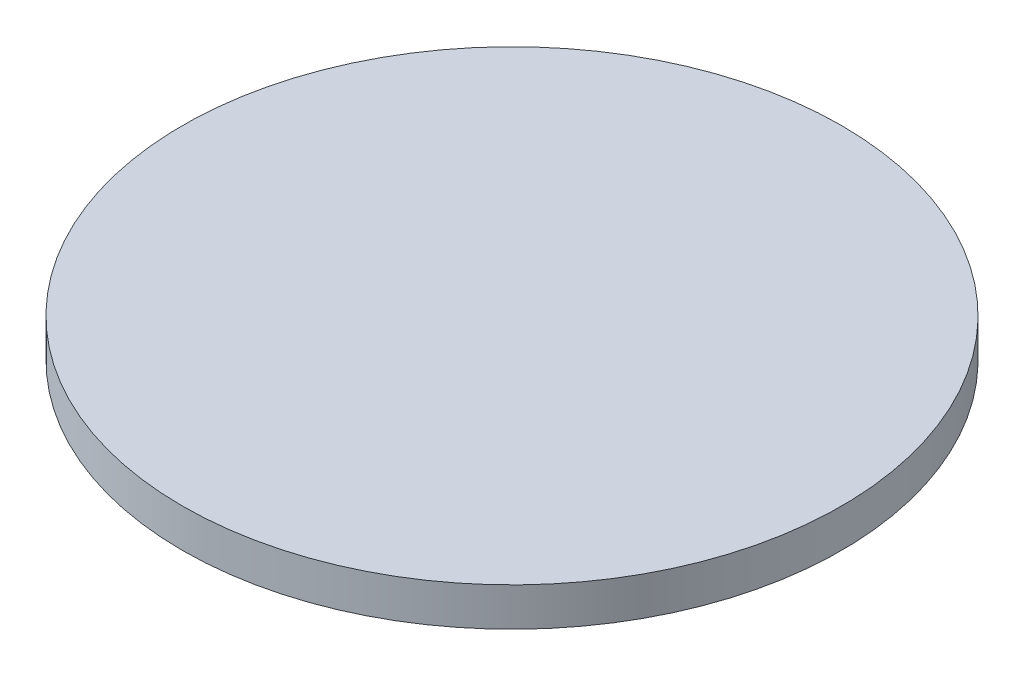
SolidWorks part; units mm, degrees
ref_plane "Front Plane" through (0, 0, 0) normal (0, 0, 1) x (1, 0, 0)
ref_plane "Top Plane" through (0, 0, 0) normal (0, 1, 0) x (1, 0, 0)
ref_plane "Right Plane" through (0, 0, 0) normal (1, 0, 0) x (0, 0, -1)
sketch "Sketch1" plane through (0, 0, 0) normal (0, 1, 0) x (1, 0, 0)
  line L0 (0, 0) -> (-60, 0) construction
  line L1 (0, 0) -> (30, 51.9615) construction
  line L2 (0, 0) -> (30, -51.9615) construction
  circle A0 centre (0, 0) radius 60
  circle A1 centre (-46.8, -15) radius 7 construction
  circle A2 centre (-46.8, 15) radius 7
  circle A3 centre (10.4096, 48.03) radius 7 construction
  circle A4 centre (36.3904, 33.03) radius 7
  circle A5 centre (36.3904, -33.03) radius 7 construction
  circle A6 centre (10.4096, -48.03) radius 7
  dimension "D1" = 30
  dimension "D3" = 14
  dimension "D2" = 46.8
  dimension "D4" = 120
  dimension "D5" = 3
extrude "Boss-Extrude1" add sketch "Sketch1" along normal blind 7 contours A0
